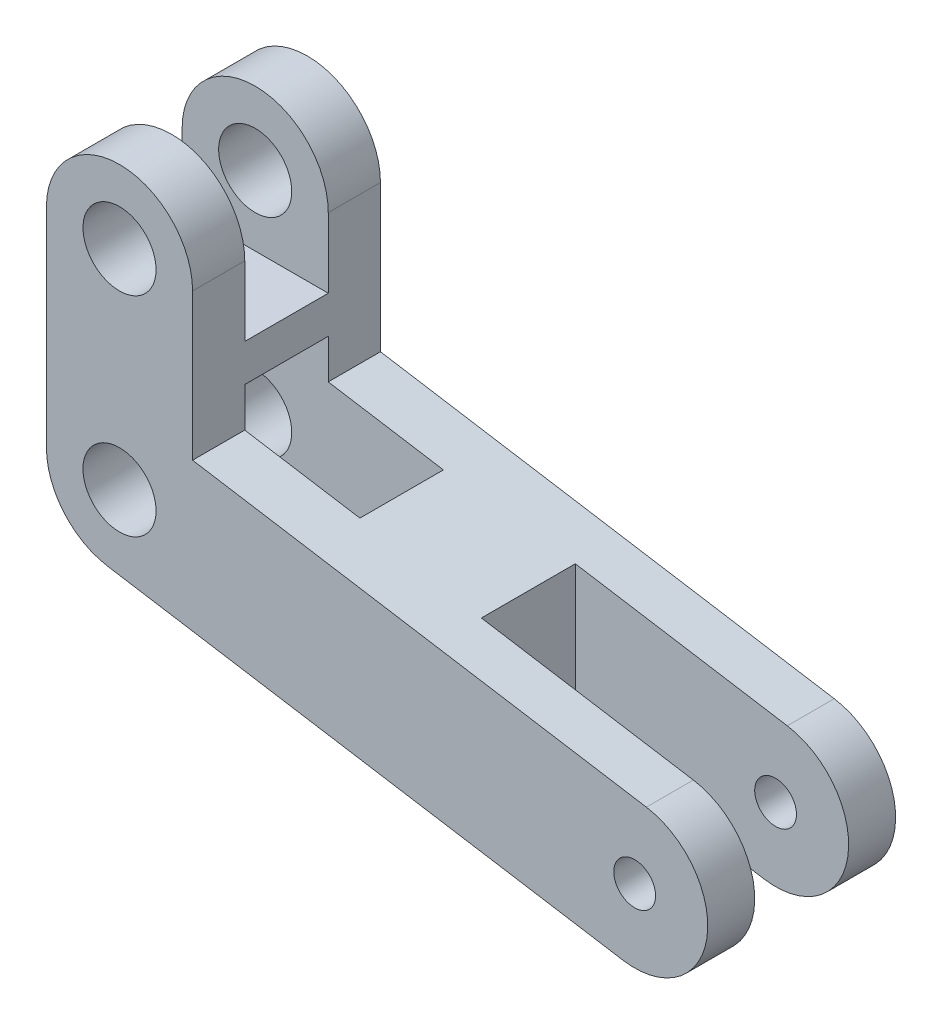
SolidWorks part; units mm, degrees
ref_plane "前视基准面" through (0, 0, 0) normal (0, 0, 1) x (1, 0, 0)
ref_plane "上视基准面" through (0, 0, 0) normal (0, 1, 0) x (1, 0, 0)
ref_plane "右视基准面" through (0, 0, 0) normal (1, 0, 0) x (0, 0, -1)
other "Configuration Table"
sketch "草图1" plane through (0, 0, 0) normal (0, 0, 1) x (1, 0, 0)
  line L0 (0, 10) -> (0, 1.75) construction
  line L1 (24.1179, -7.4549) -> (-0.56, -3.4549)
  line L2 (-3.5, 10) -> (-3.5, 0)
  line L3 (3.5, 10) -> (3.5, 2.9784)
  line L8 (25.2379, -0.5451) -> (3.5, 2.9784)
  line L9 (24.6779, -3) -> (24.6779, -4) construction
  circle A0 centre (0, 0) radius 1.75
  arc A1 (-3.5, 0) -> (-0.56, -3.4549) centre (0, 0) ccw
  arc A2 (3.5, 10) -> (-3.5, 10) centre (0, 10) ccw
  circle A4 centre (0, 10) radius 1.75
  arc A5 (24.1179, -7.4549) -> (25.2379, -0.5451) centre (24.6779, -4) ccw
  circle A6 centre (24.6779, -4) radius 1
  dimension "D1" = 10
  dimension "D2" = 3.5
  dimension "D3" = 7
  dimension "D8" = 2
  dimension "D4" = 25
  dimension "D5" = 4
extrude "凸台-拉伸1" add sketch "草图1" along normal mid plane 9
sketch "草图5" plane through (0, 0, 0) normal (0, 0, 1) x (1, 0, 0)
  line L1 (-5.6997, 16.4699) -> (3.5, 16.4699)
  line L2 (-5.6997, 16.4699) -> (-5.6997, 6.6567)
  line L3 (-5.6997, 6.6567) -> (3.5, 6.6567)
  line L4 (3.5, 16.4699) -> (3.5, 6.6567)
  line L5 (-5.6455, -5.6561) -> (9.0148, -5.6561)
  line L6 (-5.6455, -5.6561) -> (-5.6455, 4.8693)
  line L7 (-5.6455, 4.8693) -> (9.0148, 4.8693)
  line L8 (9.0148, -5.6561) -> (9.0148, 4.8693)
extrude "切除-拉伸3" cut sketch "草图5" against normal mid plane 4
sketch "草图6" plane through (0, 0, 0) normal (0, 0, 1) x (1, 0, 0)
  line L1 (34.2713, -10) -> (15.0845, -10)
  line L2 (34.2713, -10) -> (34.2713, 2)
  line L3 (34.2713, 2) -> (15.0845, 2)
  line L4 (15.0845, -10) -> (15.0845, 2)
  line L5 (34.2713, -10) -> (15.0845, 2) construction
  line L6 (34.2713, 2) -> (15.0845, -10) construction
  point P0 (24.6779, -4)
  dimension "D1" = 6
extrude "切除-拉伸4" cut sketch "草图6" against normal mid plane 4.5
